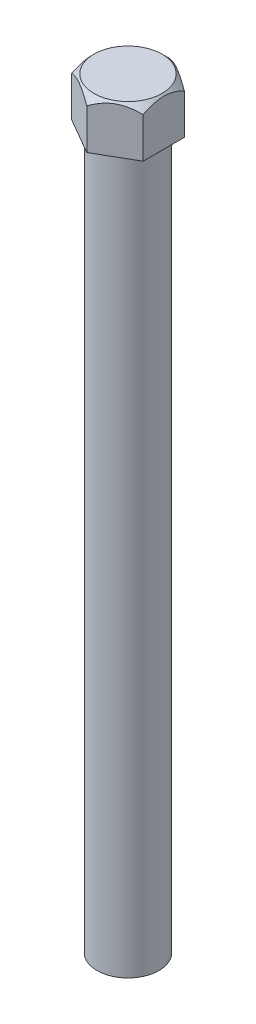
SolidWorks part; units mm, degrees
ref_plane "Front Plane" through (0, 0, 0) normal (0, 0, 1) x (1, 0, 0)
ref_plane "Top Plane" through (0, 0, 0) normal (0, 1, 0) x (1, 0, 0)
ref_plane "Right Plane" through (0, 0, 0) normal (1, 0, 0) x (0, 0, -1)
sketch "Sketch2" plane through (0, 0, 0) normal (0, 1, 0) x (1, 0, 0)
  circle A0 centre (0, 0) radius 3.302
  dimension "D1" = 6.604
extrude "Boss-Extrude1" add sketch "Sketch2" along normal mid plane 81.28
sketch "Sketch3" plane through (0, 40.64, 0) normal (0, 1, 0) x (1, 0, 0)
  line L1 (3.81, 2.1997) -> (0, 4.3994)
  line L2 (0, 4.3994) -> (-3.81, 2.1997)
  line L3 (-3.81, 2.1997) -> (-3.81, -2.1997)
  line L4 (-3.81, -2.1997) -> (0, -4.3994)
  line L5 (0, -4.3994) -> (3.81, -2.1997)
  line L6 (3.81, -2.1997) -> (3.81, 2.1997)
  circle A0 centre (0, 0) radius 3.81 construction
  point P1 (0, 0)
  dimension "D1" = 7.62
extrude "Boss-Extrude2" add sketch "Sketch3" against normal blind 5.08
ref_plane "Plane1" through (0, 0, 0) normal (0.5, 0, 0.866) x (0.866, 0, -0.5)
sketch "Sketch6" plane through (0, 0, 0) normal (0.5, 0, 0.866) x (0.866, 0, -0.5)
  line L0 (-3.6374, 40.64) -> (-4.3994, 40.64)
  line L1 (-4.3994, 40.64) -> (-4.3994, 39.878)
  line L2 (-4.3994, 39.878) -> (-3.6374, 40.64)
  line L3 (0, 0) -> (0, 12.6844) construction
  dimension "D1" = 0.762
  dimension "D2" = 0.762
revolve "Cut-Revolve1" cut sketch "Sketch6" angle 360 about L3
